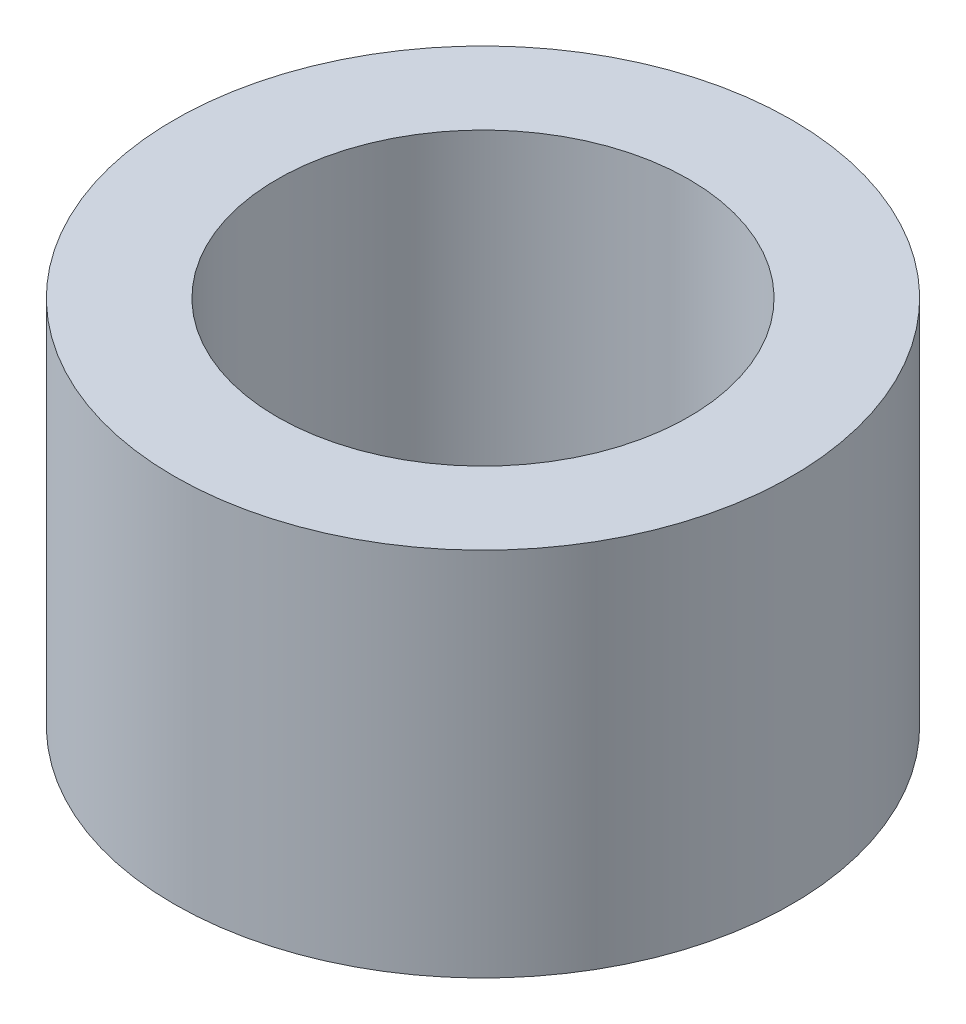
SolidWorks part; units mm, degrees
ref_plane "Спереди" through (0, 0, 0) normal (0, 0, 1) x (1, 0, 0)
ref_plane "Сверху" through (0, 0, 0) normal (0, 1, 0) x (1, 0, 0)
ref_plane "Справа" through (0, 0, 0) normal (1, 0, 0) x (0, 0, -1)
sketch "Эскиз1" plane through (0, 0, 0) normal (0, 1, 0) x (1, 0, 0)
  circle A0 centre (0, 0) radius 2
  circle A1 centre (0, 0) radius 3
  dimension "D1" = 4
  dimension "D2" = 6
extrude "Бобышка-Вытянуть1" add sketch "Эскиз1" along normal blind 3.6
